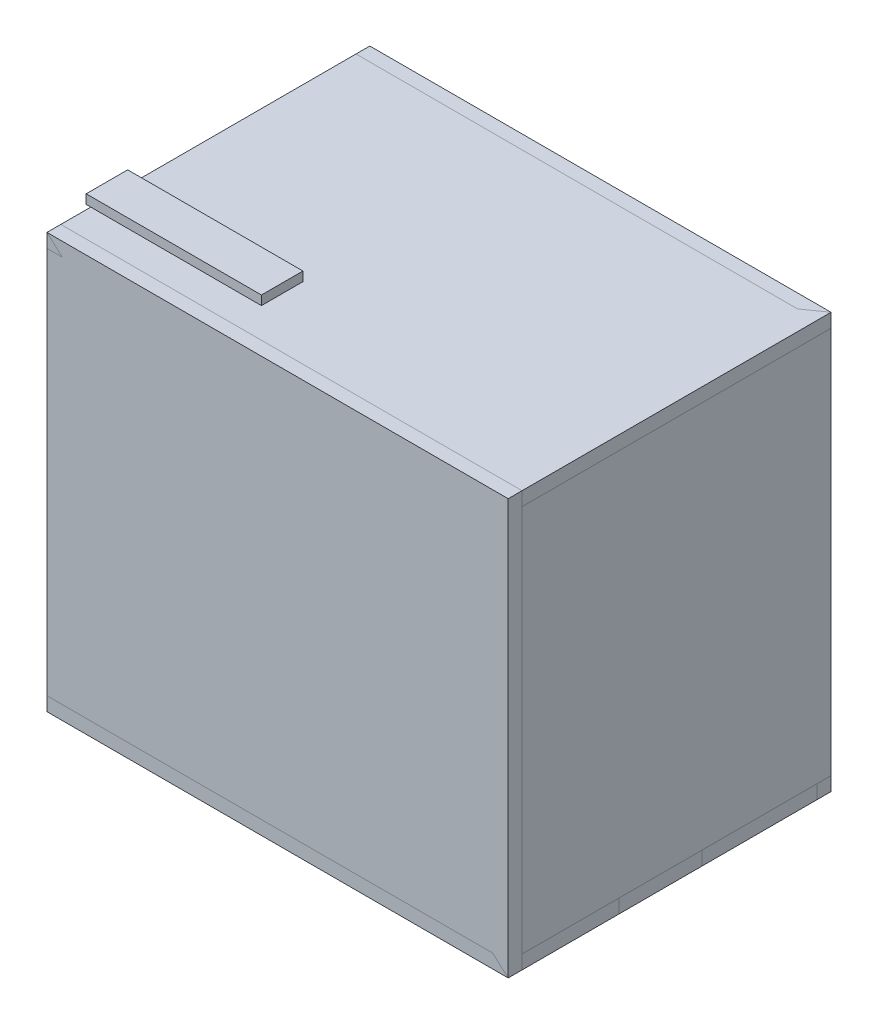
SolidWorks part; units mm, degrees
ref_plane "前视基准面" through (0, 0, 0) normal (0, 0, 1) x (1, 0, 0)
ref_plane "上视基准面" through (0, 0, 0) normal (0, 1, 0) x (1, 0, 0)
ref_plane "右视基准面" through (0, 0, 0) normal (1, 0, 0) x (0, 0, -1)
other "Configuration Table"
sketch "草图1" plane through (0, 0, 0) normal (0, 0, 1) x (1, 0, 0)
  line L1 (-50, -45) -> (50, -45)
  line L2 (-50, -45) -> (-50, 45)
  line L3 (-50, 45) -> (50, 45)
  line L4 (50, -45) -> (50, 45)
  line L5 (-50, -45) -> (50, 45) construction
  line L6 (-50, 45) -> (50, -45) construction
  point P0 (0, 0)
extrude "bottom plate - 100 x 90 x 3 mm" add sketch "草图1" along normal blind 3 from offset 35 separate body
sketch "草图2" plane through (0, 0, 0) normal (0, 0, 1) x (1, 0, 0)
  line L1 (-50, 42) -> (50, 42)
  line L2 (-50, 42) -> (-50, 45)
  line L3 (-50, 45) -> (50, 45)
  line L4 (50, 42) -> (50, 45)
  line L5 (-50, 42) -> (50, 45) construction
  line L6 (-50, 45) -> (50, 42) construction
  point P0 (0, 43.5)
extrude "back wall - 3 mm" add sketch "草图2" along normal blind 70 from offset 35 separate body
sketch "草图3" plane through (0, 0, 0) normal (0, 0, 1) x (1, 0, 0)
  line L0 (-50, 42) -> (50, 42) construction
  line L1 (-50, -42) -> (-47, -42)
  line L2 (-50, -42) -> (-50, 42)
  line L3 (-50, 42) -> (-47, 42)
  line L4 (-47, -42) -> (-47, 42)
  line L5 (-50, -42) -> (-47, 42) construction
  line L6 (-50, 42) -> (-47, -42) construction
  point P0 (-48.5, 0)
extrude "left side wall - 3 mm" add sketch "草图3" along normal blind 70 from offset 35 separate body
sketch "草图4" plane through (0, 0, 0) normal (0, 0, 1) x (1, 0, 0)
  line L1 (47, -42) -> (50, -42)
  line L2 (47, -42) -> (47, 42)
  line L3 (47, 42) -> (50, 42)
  line L4 (50, -42) -> (50, 42)
  line L5 (47, -42) -> (50, 42) construction
  line L6 (47, 42) -> (50, -42) construction
  point P0 (48.5, 0)
extrude "right side wall - 3 mm" add sketch "草图4" along normal blind 70 from offset 35 separate body
sketch "草图5" plane through (0, 0, 0) normal (0, 0, 1) x (1, 0, 0)
  line L1 (-50, -45) -> (50, -45)
  line L2 (-50, -45) -> (-50, -42)
  line L3 (-50, -42) -> (50, -42)
  line L4 (50, -45) -> (50, -42)
  line L5 (-50, -45) -> (50, -42) construction
  line L6 (-50, -42) -> (50, -45) construction
  point P0 (0, -43.5)
extrude "front wall lower frame below HC-SR04 window" add sketch "草图5" along normal blind 28 from offset 35 separate body
sketch "草图6" plane through (0, 0, 0) normal (0, 0, 1) x (1, 0, 0)
  line L1 (-50, -45) -> (50, -45)
  line L2 (-50, -45) -> (-50, -42)
  line L3 (-50, -42) -> (50, -42)
  line L4 (50, -45) -> (50, -42)
  line L5 (-50, -45) -> (50, -42) construction
  line L6 (-50, -42) -> (50, -45) construction
  point P0 (0, -43.5)
extrude "front wall upper frame above HC-SR04 window" add sketch "草图6" along normal blind 24 from offset 11 separate body
sketch "草图7" plane through (0, 0, 0) normal (0, 0, 1) x (1, 0, 0)
  line L0 (50, -42) -> (-50, -42) construction
  line L1 (-50, -45) -> (-23, -45)
  line L2 (-50, -45) -> (-50, -42)
  line L3 (-50, -42) -> (-23, -42)
  line L4 (-23, -45) -> (-23, -42)
  line L5 (-50, -45) -> (-23, -42) construction
  line L6 (-50, -42) -> (-23, -45) construction
  point P0 (-36.5, -43.5)
extrude "front wall left frame" add sketch "草图7" along normal blind 18 from offset 7 separate body
sketch "草图8" plane through (0, 0, 0) normal (0, 0, 1) x (1, 0, 0)
  line L1 (23, -45) -> (50, -45)
  line L2 (23, -45) -> (23, -42)
  line L3 (23, -42) -> (50, -42)
  line L4 (50, -45) -> (50, -42)
  line L5 (23, -45) -> (50, -42) construction
  line L6 (23, -42) -> (50, -45) construction
  point P0 (36.5, -43.5)
extrude "front wall right frame" add sketch "草图8" along normal blind 18 from offset 7 separate body
sketch "草图9" plane through (0, 0, 0) normal (0, 0, 1) x (1, 0, 0)
  line L1 (-50, -45) -> (50, -45)
  line L2 (-50, -45) -> (-50, 45)
  line L3 (-50, 45) -> (50, 45)
  line L4 (50, -45) -> (50, 45)
  line L5 (-50, -45) -> (50, 45) construction
  line L6 (-50, 45) -> (50, -45) construction
  point P0 (0, 0)
extrude "transparent top lid - removable" add sketch "草图9" along normal blind 3 from offset 32 separate body
sketch "草图10" plane through (0, 0, 0) normal (0, 0, 1) x (1, 0, 0)
  line L1 (-18, -14) -> (18, -14)
  line L2 (-18, -14) -> (-18, 14)
  line L3 (-18, 14) -> (18, 14)
  line L4 (18, -14) -> (18, 14)
  line L5 (-18, -14) -> (18, 14) construction
  line L6 (-18, 14) -> (18, -14) construction
  point P0 (0, 0)
extrude "servo support platform - 36 x 28 x 4 mm" add sketch "草图10" along normal blind 4 from offset 6 separate body
sketch "草图11" plane through (0, 0, 0) normal (0, 0, 1) x (1, 0, 0)
  line L1 (-32, -18) -> (32, -18)
  line L2 (-32, -18) -> (-32, 26)
  line L3 (-32, 26) -> (32, 26)
  line L4 (32, -18) -> (32, 26)
  line L5 (-32, -18) -> (32, 26) construction
  line L6 (-32, 26) -> (32, -18) construction
  point P0 (0, 4)
extrude "battery tray base - 60 x 40 mm" add sketch "草图11" along normal blind 2 from offset 27 separate body
sketch "草图12" plane through (0, 0, 0) normal (0, 0, 1) x (1, 0, 0)
  circle A0 centre (-32, -24) radius 3
extrude "PCB standoff 1 - M3 clearance marker" add sketch "草图12" along normal blind 14 from offset 33 separate body
sketch "草图13" plane through (0, 0, 0) normal (0, 0, 1) x (1, 0, 0)
  circle A0 centre (32, -24) radius 3
extrude "PCB standoff 2 - M3 clearance marker" add sketch "草图13" along normal blind 14 from offset 33 separate body
sketch "草图14" plane through (0, 0, 0) normal (0, 0, 1) x (1, 0, 0)
  line L0 (-32, 26) -> (-32, -18) construction
  circle A0 centre (-32, 24) radius 3
extrude "PCB standoff 3 - M3 clearance marker" add sketch "草图14" along normal blind 14 from offset 33 separate body
sketch "草图15" plane through (0, 0, 0) normal (0, 0, 1) x (1, 0, 0)
  line L0 (32, -18) -> (32, 26) construction
  circle A0 centre (32, 24) radius 3
extrude "PCB standoff 4 - M3 clearance marker" add sketch "草图15" along normal blind 14 from offset 33 separate body
sketch "草图16" plane through (0, 0, 0) normal (0, 0, 1) x (1, 0, 0)
  line L1 (-49, 47) -> (-11, 47)
  line L2 (-49, 47) -> (-49, 49)
  line L3 (-49, 49) -> (-11, 49)
  line L4 (-11, 47) -> (-11, 49)
  line L5 (-49, 47) -> (-11, 49) construction
  line L6 (-49, 49) -> (-11, 47) construction
  point P0 (-30, 48)
extrude "case label plate - CASE 100x90x70" add sketch "草图16" along normal blind 9 from offset 18.5 separate body
